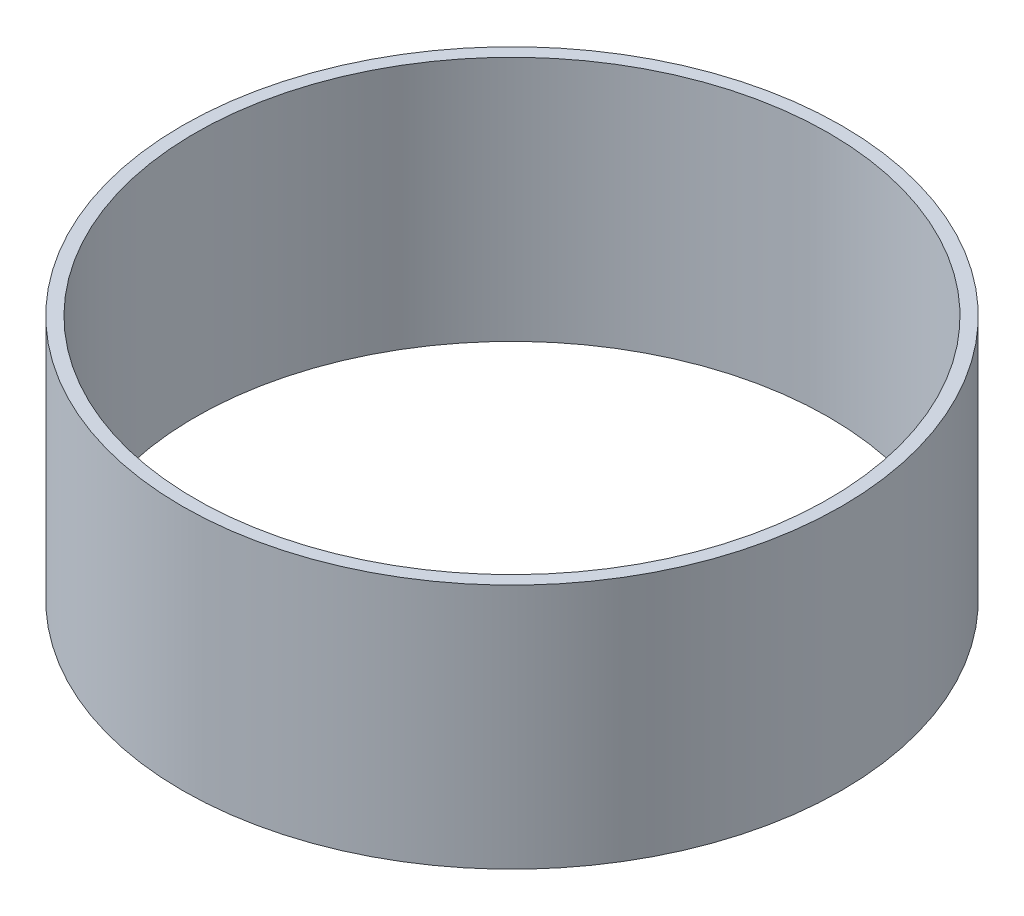
SolidWorks part; units mm, degrees
ref_plane "Front Plane" through (0, 0, 0) normal (0, 0, 1) x (1, 0, 0)
ref_plane "Top Plane" through (0, 0, 0) normal (0, 1, 0) x (1, 0, 0)
ref_plane "Right Plane" through (0, 0, 0) normal (1, 0, 0) x (0, 0, -1)
sketch "Sketch2" plane through (0, 0, 0) normal (0, 1, 0) x (1, 0, 0)
  circle A0 centre (0, 0) radius 49.0601
  circle A1 centre (0, 0) radius 51.054
  dimension "D1" = 102.108
  dimension "D2" = 98.1202
extrude "Boss-Extrude1" add sketch "Sketch2" along normal blind 38.1
